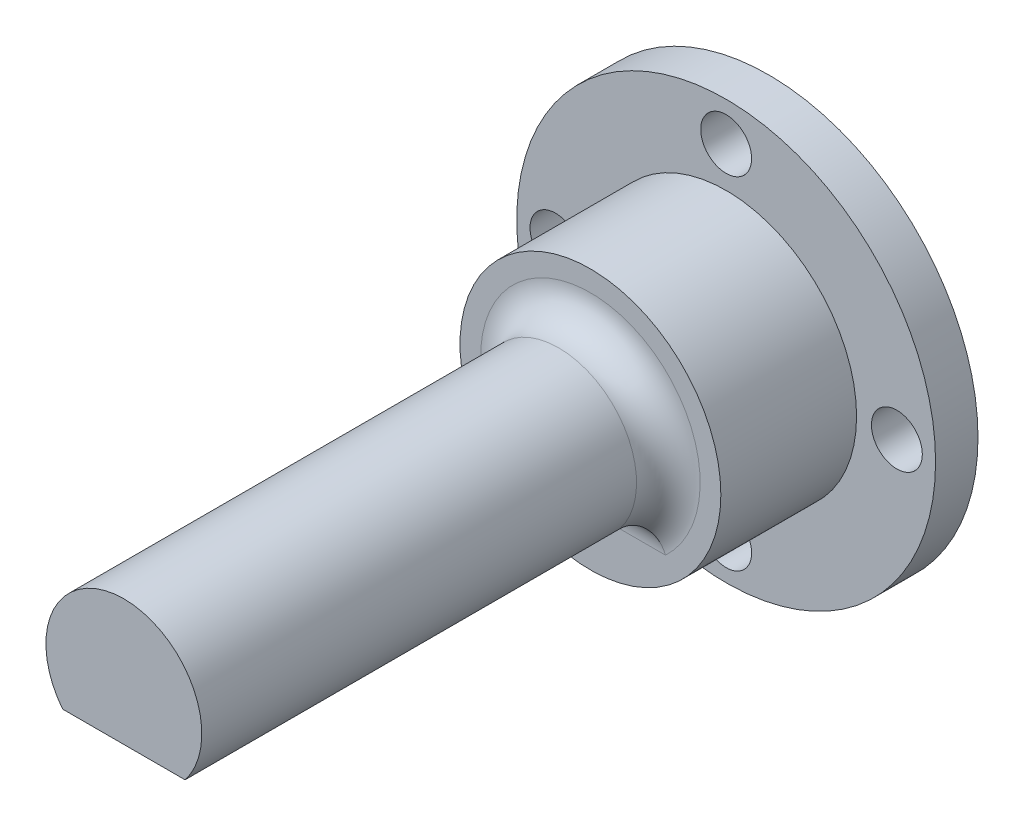
SolidWorks part; units mm, degrees
ref_plane "Plan de face" through (0, 0, 0) normal (0, 0, 1) x (1, 0, 0)
ref_plane "Plan de dessus" through (0, 0, 0) normal (0, 1, 0) x (1, 0, 0)
ref_plane "Plan de droite" through (0, 0, 0) normal (1, 0, 0) x (0, 0, -1)
sketch "Esquisse1" plane through (0, 0, 0) normal (0, 0, 1) x (1, 0, 0)
  circle A0 centre (0, 0) radius 9.875
  dimension "D1" = 19.75
extrude "Boss.-Extru.1" add sketch "Esquisse1" along normal blind 2
sketch "Esquisse2" plane through (0, 0, 2) normal (0, 0, 1) x (1, 0, 0)
  circle A0 centre (0, 0) radius 6.15
  dimension "D1" = 12.3
extrude "Boss.-Extru.2" add sketch "Esquisse2" along normal blind 6.4
sketch "Esquisse3" plane through (0, 0, 8.4) normal (0, 0, 1) x (1, 0, 0)
  circle A0 centre (0, 0) radius 3.675
  dimension "D1" = 7.35
extrude "Boss.-Extru.3" add sketch "Esquisse3" along normal blind 22
sketch "Esquisse4" plane through (0, 0, 30.4) normal (0, 0, 1) x (1, 0, 0)
  line L0 (-2.8862, -2.275) -> (2.8862, -2.275)
  circle A0 centre (0, 0) radius 3.675 construction
  circle A1 centre (0, 0) radius 3.675 construction
  arc A2 (-2.8862, -2.275) -> (2.8862, -2.275) centre (0, 0) ccw
  dimension "D1" = 2.275
extrude "Enlèv. mat.-Extru.1" cut sketch "Esquisse4" against normal blind 22
sketch "Esquisse5" plane through (0, 0, 2) normal (0, 0, 1) x (1, 0, 0)
  circle A0 centre (0, 8.0453) radius 1.2
  circle A1 centre (0, -8.0547) radius 1.2
  circle A2 centre (0, 0) radius 9.875 construction
  circle A3 centre (-8.05, 0) radius 1.2
  circle A4 centre (8.05, 0) radius 1.2
  dimension "D1" = 2.4
  dimension "D2" = 2.4
  dimension "D6" = 2.4
  dimension "D7" = 2.4
  dimension "D3" = 16.1
  dimension "D4" = 8.0453
  dimension "D5" = 8.0547
  dimension "D8" = 16.1
  dimension "D9" = 8.05
  dimension "D10" = 8.05
extrude "Enlèv. mat.-Extru.2" cut sketch "Esquisse5" against normal through all
fillet "Congé1" radius 1.5 2 edges at (0, -2.275, 8.4) (0, 3.675, 8.4)
